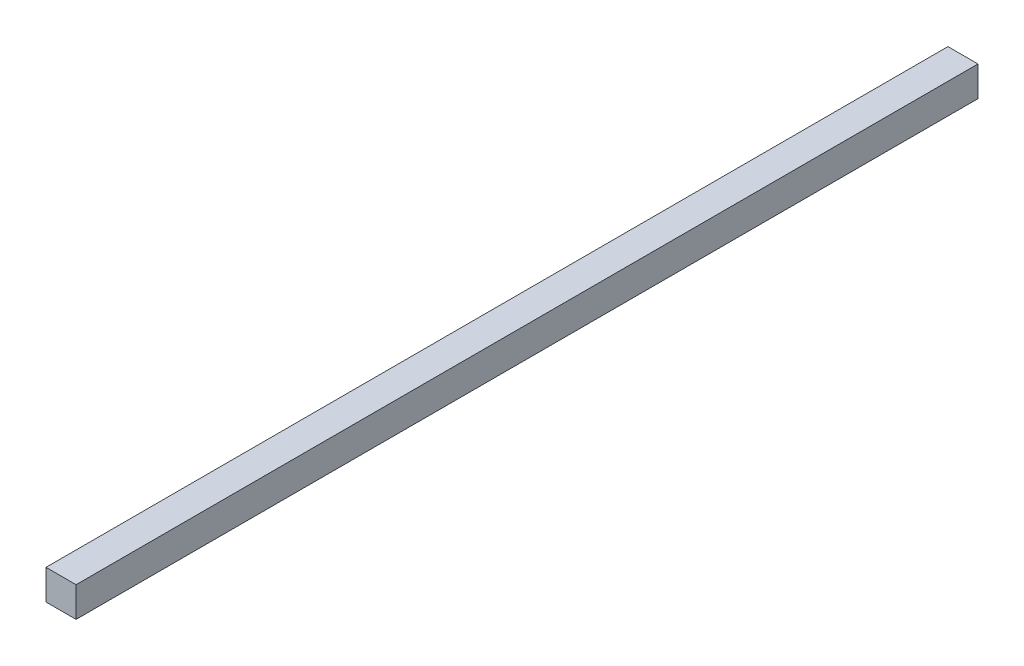
SolidWorks part; units mm, degrees
material "Plain Carbon Steel"
ref_plane "Front Plane" through (0, 0, 0) normal (0, 0, 1) x (1, 0, 0)
ref_plane "Top Plane" through (0, 0, 0) normal (0, 1, 0) x (1, 0, 0)
ref_plane "Right Plane" through (0, 0, 0) normal (1, 0, 0) x (0, 0, -1)
sketch "Sketch1" plane through (0, 0, 0) normal (0, 0, 1) x (1, 0, 0)
  line L1 (0, 0) -> (20, 0)
  line L2 (0, 0) -> (0, -20)
  line L3 (0, -20) -> (20, -20)
  line L4 (20, 0) -> (20, -20)
  dimension "D1" = 20
extrude "Boss-Extrude1" add sketch "Sketch1" along normal blind 600
